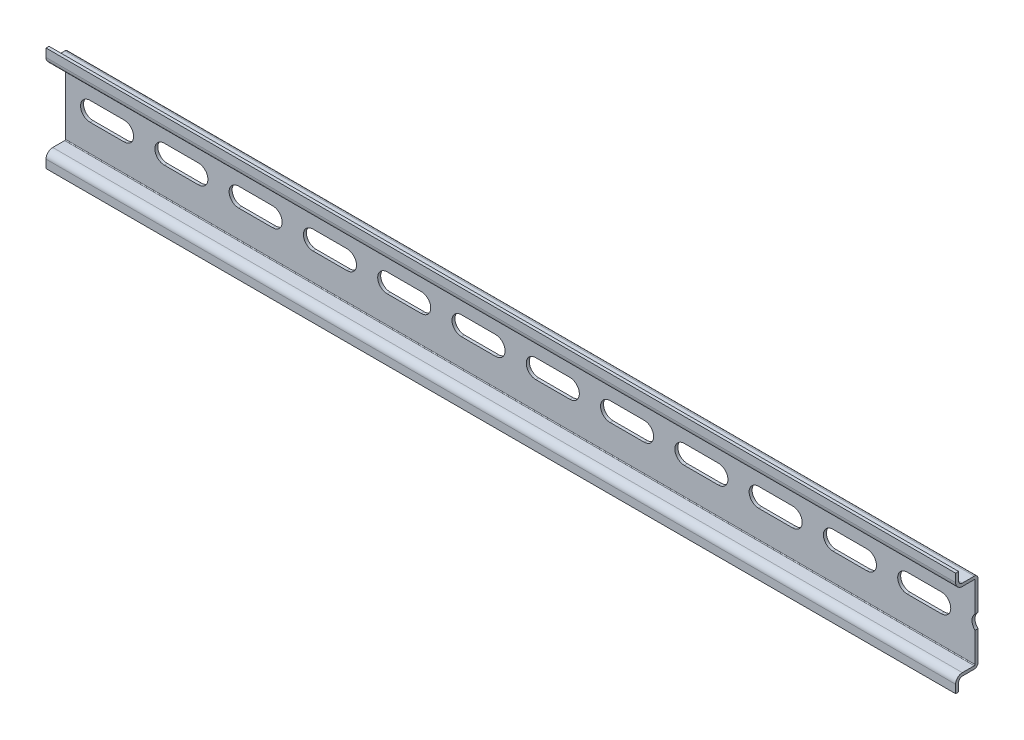
SolidWorks part; units mm, degrees
ref_plane "Front Plane" through (0, 0, 0) normal (0, 0, 1) x (1, 0, 0)
ref_plane "Top Plane" through (0, 0, 0) normal (0, 1, 0) x (1, 0, 0)
ref_plane "Right Plane" through (0, 0, 0) normal (1, 0, 0) x (0, 0, -1)
sketch "Sketch1" plane through (0, 0, 0) normal (0, 1, 0) x (1, 0, 0)
  line L0 (-152.4, 0) -> (152.4, 0)
  point P3 (0, 0)
  dimension "D1" = 304.8
other "Structural Member1"
ref_plane "Plane1" through (-152.4, 0, 0) normal (1, 0, 0) x (0, 0, -1)
sketch "Sketch2" plane through (-152.4, 0, 0) normal (1, 0, 0) x (0, 0, -1)
  line L0 (0, 12.25) -> (0, -12.25)
  line L1 (-1.25, 13.5) -> (-5.25, 13.5)
  line L2 (-6.5, 14.75) -> (-6.5, 17.5)
  line L3 (0, 0) -> (-1, 0) construction
  line L4 (-6.5, -14.75) -> (-6.5, -17.5)
  line L5 (-1.25, -13.5) -> (-5.25, -13.5)
  line L6 (-7.5, 14.75) -> (-7.5, 17.5)
  line L7 (-1.25, 12.5) -> (-5.25, 12.5)
  line L8 (-1, 12.25) -> (-1, -12.25)
  line L9 (-1.25, -12.5) -> (-5.25, -12.5)
  line L10 (-7.5, -14.75) -> (-7.5, -17.5)
  line L11 (-6.5, 17.5) -> (-7.5, 17.5)
  line L12 (-6.5, -17.5) -> (-7.5, -17.5)
  arc A0 (-5.25, 13.5) -> (-6.5, 14.75) centre (-5.25, 14.75) cw
  arc A1 (-6.5, -14.75) -> (-5.25, -13.5) centre (-5.25, -14.75) cw
  arc A2 (0, -12.25) -> (-1.25, -13.5) centre (-1.25, -12.25) cw
  arc A3 (0, 12.25) -> (-1.25, 13.5) centre (-1.25, 12.25) ccw
  arc A4 (-5.25, 12.5) -> (-7.5, 14.75) centre (-5.25, 14.75) cw
  arc A5 (-1, 12.25) -> (-1.25, 12.5) centre (-1.25, 12.25) ccw
  arc A6 (-1, -12.25) -> (-1.25, -12.5) centre (-1.25, -12.25) cw
  arc A7 (-7.5, -14.75) -> (-5.25, -12.5) centre (-5.25, -14.75) cw
  point P3 (0, 0)
  point P12 (-6.5, 13.5)
  point P15 (-6.5, -13.5)
  point P18 (0, -13.5)
  point P21 (0, 13.5)
  point P36 (0, 0)
  dimension "D4" = 1.25
  dimension "D1" = 35
  dimension "D2" = 27
  dimension "D3" = 7.5
  dimension "D5" = 1
sketch "Sketch3" plane through (0, 0, 0) normal (0, 0, 1) x (1, 0, 0)
  line L0 (-144.145, 0) -> (-132.715, 0) construction
  line L1 (-144.145, 3.175) -> (-132.715, 3.175)
  line L2 (-144.145, -3.175) -> (-132.715, -3.175)
  line L3 (-152.4, 12.25) -> (-152.4, -12.25) construction
  arc A0 (-144.145, 3.175) -> (-144.145, -3.175) centre (-144.145, 0) ccw
  arc A1 (-132.715, -3.175) -> (-132.715, 3.175) centre (-132.715, 0) ccw
  point P2 (-138.43, 0)
  dimension "D1" = 5.08
  dimension "D2" = 17.78
  dimension "D3" = 3.175
extrude "Cut-Extrude1" cut sketch "Sketch3" along normal up to next
pattern_linear "LPattern1" count 13 spacing 24.892 along (1, 0, 0) of "Cut-Extrude1"
equation "\"D1@LPattern1\" = \"RD1@Annotations\" + 1"
